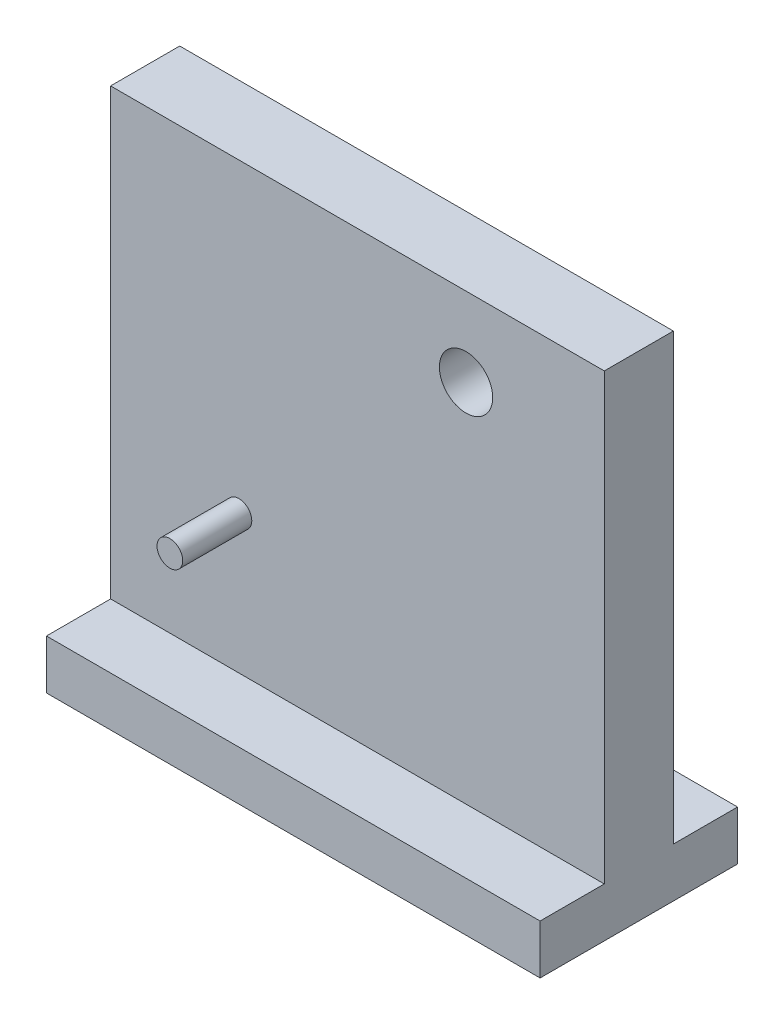
SolidWorks part; units mm, degrees
ref_plane "前视基准面" through (0, 0, 0) normal (0, 0, 1) x (1, 0, 0)
ref_plane "上视基准面" through (0, 0, 0) normal (0, 1, 0) x (1, 0, 0)
ref_plane "右视基准面" through (0, 0, 0) normal (1, 0, 0) x (0, 0, -1)
sketch "草图1" plane through (0, 0, 0) normal (0, 0, 1) x (1, 0, 0)
  line L1 (-20, 50) -> (20, 50)
  line L2 (-20, 50) -> (-20, 0)
  line L3 (-20, 0) -> (20, 0)
  line L4 (20, 50) -> (20, 0)
  line L5 (-20, 50) -> (20, 0) construction
  line L6 (-20, 0) -> (20, 50) construction
  circle A0 centre (6, 22) radius 2.5 construction
  circle A1 centre (6, 42) radius 2.7
  point P0 (0, 25)
  dimension "D2" = 5
  dimension "D6" = 5.4
  dimension "D1" = 40
  dimension "D3" = 22
  dimension "D4" = 6
  dimension "D5" = 20
  dimension "D7" = 8
extrude "凸台-拉伸1" add sketch "草图1" along normal mid plane 7
sketch "草图3" plane through (0, 0, 0) normal (0, 0, 1) x (1, 0, 0)
  line L0 (20, 0) -> (20, 50) construction
  line L1 (-20, 0) -> (20, 0)
  line L2 (-20, 0) -> (-20, 5)
  line L3 (-20, 5) -> (20, 5)
  line L4 (20, 0) -> (20, 5)
  dimension "D1" = 5
extrude "凸台-拉伸2" add sketch "草图3" along normal mid plane 20
sketch "草图7" plane through (-20, 0, 0) normal (-1, 0, 0) x (0, 0, 1)
  line L8 (-10, 0) -> (10, 0)
  line L9 (10, 0) -> (10, 5)
  line L10 (10, 5) -> (3.5, 5)
  line L11 (3.5, 5) -> (3.5, 50)
  line L12 (3.5, 50) -> (-3.5, 50)
  line L13 (-3.5, 50) -> (-3.5, 5)
  line L14 (-3.5, 5) -> (-10, 5)
  line L15 (-10, 5) -> (-10, 0)
  line L16 (-10, 0) -> (10, 0)
  line L17 (10, 0) -> (10, 5)
  line L18 (10, 5) -> (3.5, 5)
  line L19 (3.5, 5) -> (3.5, 50)
  line L20 (3.5, 50) -> (-3.5, 50)
  line L21 (-3.5, 50) -> (-3.5, 5)
  line L22 (-3.5, 5) -> (-10, 5)
  line L23 (-10, 5) -> (-10, 0)
  dimension "D1" = 0
extrude "凸台-拉伸3" add sketch "草图7" along normal blind 10
sketch "草图5" plane through (0, 0, 3.5) normal (0, 0, 1) x (1, 0, 0)
  circle A0 centre (6, 42) radius 2.7 construction
  circle A1 centre (6, 42) radius 2.7 construction
  circle A2 centre (-17, 19) radius 1.3
  dimension "D3" = 2.6
  dimension "D1" = 23
  dimension "D2" = 23
extrude "凸台-拉伸4" add sketch "草图5" along normal blind 7
